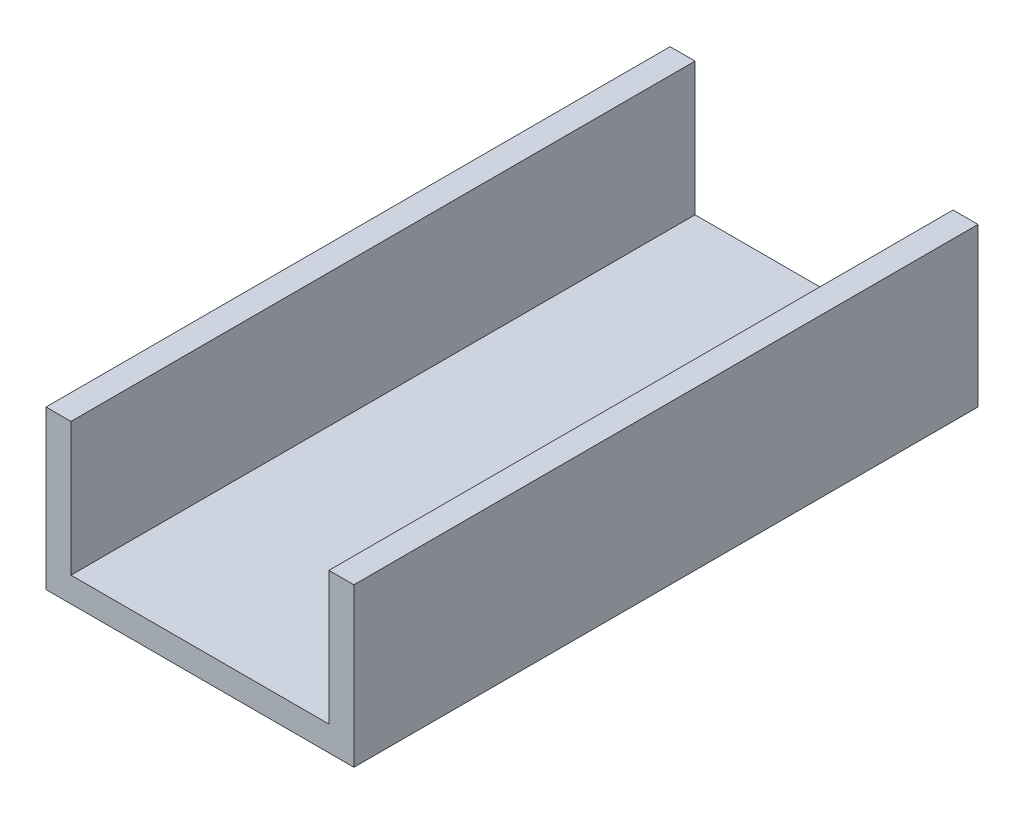
SolidWorks part; units mm, degrees
ref_plane "Plano frontal" through (0, 0, 0) normal (0, 0, 1) x (1, 0, 0)
ref_plane "Plano superior" through (0, 0, 0) normal (0, 1, 0) x (1, 0, 0)
ref_plane "Plano direito" through (0, 0, 0) normal (1, 0, 0) x (0, 0, -1)
sketch "Esboço1" plane through (0, 0, 0) normal (0, 1, 0) x (1, 0, 0)
  line L1 (-9.25, 19.5) -> (9.25, 19.5)
  line L2 (-9.25, 19.5) -> (-9.25, -19.5)
  line L3 (-9.25, -19.5) -> (9.25, -19.5)
  line L4 (9.25, 19.5) -> (9.25, -19.5)
  line L5 (-9.25, 19.5) -> (9.25, -19.5) construction
  line L6 (-9.25, -19.5) -> (9.25, 19.5) construction
  point P0 (0, 0)
  dimension "D1" = 18.5
  dimension "D2" = 39
extrude "Extrusão1" add sketch "Esboço1" along normal blind 1.5
sketch "Esboço2" plane through (0, 1.5, 0) normal (0, 1, 0) x (1, 0, 0)
  line L0 (7.75, 19.5) -> (9.25, 19.5)
  line L1 (-9.25, 19.5) -> (-7.75, 19.5)
  line L2 (-9.25, 19.5) -> (-9.25, -19.5)
  line L3 (-9.25, -19.5) -> (9.25, -19.5)
  line L4 (9.25, 19.5) -> (9.25, -19.5)
  line L6 (-7.75, 19.5) -> (-7.75, -18)
  line L7 (-7.75, -18) -> (7.75, -18)
  line L8 (7.75, 19.5) -> (7.75, -18)
  dimension "D1" = 1.5
  dimension "D2" = 1.5
  dimension "D3" = 1.5
extrude "Extrusão2" add sketch "Esboço2" along normal blind 8
sketch "Esboço3" plane through (0, 9.5, 0) normal (0, 1, 0) x (1, 0, 0)
  line L0 (9.25, -19.5) -> (9.25, 19.5) construction
  line L1 (-9.25, -19.5) -> (9.25, -19.5)
  line L2 (-9.25, -19.5) -> (-9.25, -18)
  line L3 (-9.25, -18) -> (9.25, -18)
  line L4 (9.25, -19.5) -> (9.25, -18)
extrude "Extrusão3" cut sketch "Esboço3" against normal through all
